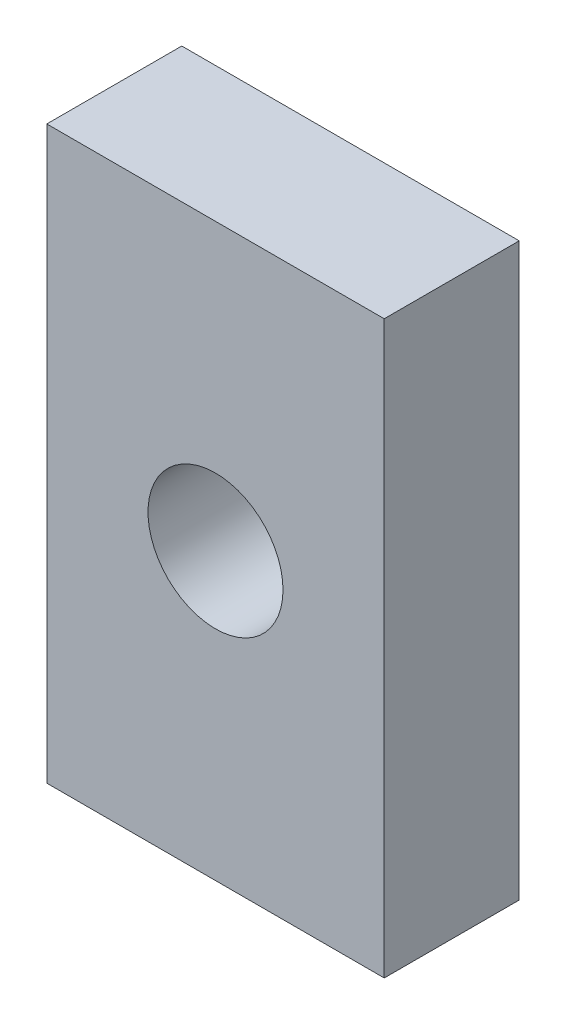
SolidWorks part; units mm, degrees
ref_plane "Front Plane" through (0, 0, 0) normal (0, 0, 1) x (1, 0, 0)
ref_plane "Top Plane" through (0, 0, 0) normal (0, 1, 0) x (1, 0, 0)
ref_plane "Right Plane" through (0, 0, 0) normal (1, 0, 0) x (0, 0, -1)
sketch "Sketch1" plane through (0, 0, 0) normal (0, 0, 1) x (1, 0, 0)
  line L1 (-12.5, -21.15) -> (12.5, -21.15)
  line L2 (-12.5, -21.15) -> (-12.5, 21.15)
  line L3 (-12.5, 21.15) -> (12.5, 21.15)
  line L4 (12.5, -21.15) -> (12.5, 21.15)
  line L5 (-12.5, -21.15) -> (12.5, 21.15) construction
  line L6 (-12.5, 21.15) -> (12.5, -21.15) construction
  circle A0 centre (0, 0) radius 5
  point P0 (0, 0)
  dimension "D3" = 10
  dimension "D1" = 21.15
extrude "Boss-Extrude1" add sketch "Sketch1" along normal blind 10
